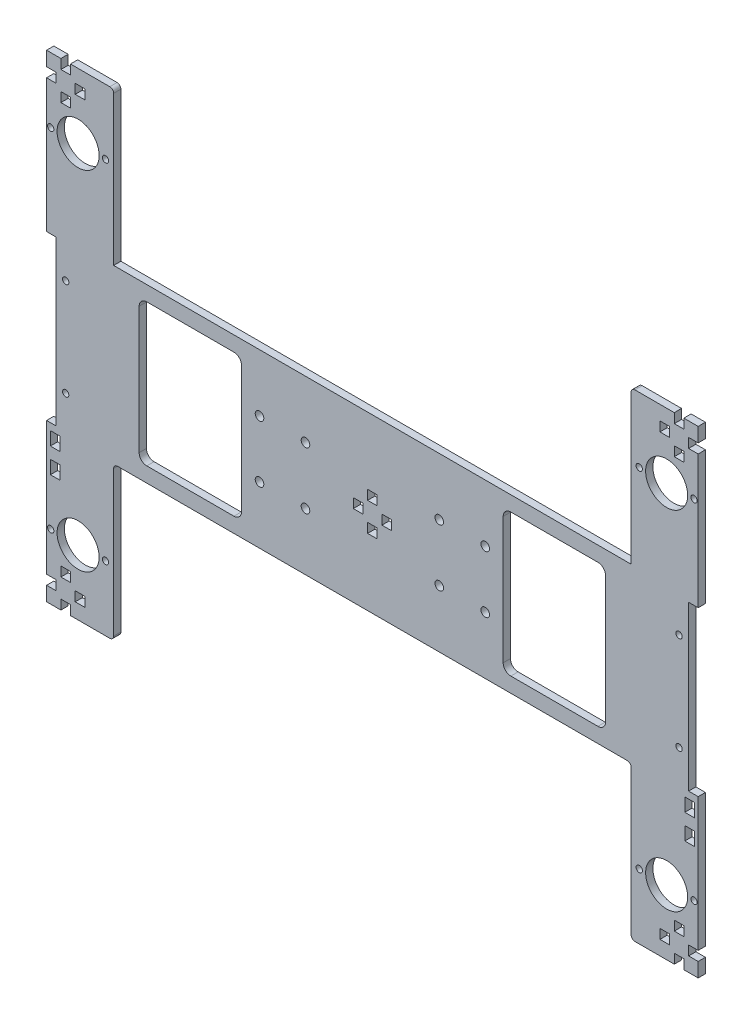
SolidWorks part; units mm, degrees
ref_plane "Front Plane" through (0, 0, 0) normal (0, 0, 1) x (1, 0, 0)
ref_plane "Top Plane" through (0, 0, 0) normal (0, 1, 0) x (1, 0, 0)
ref_plane "Right Plane" through (0, 0, 0) normal (1, 0, 0) x (0, 0, -1)
ref_plane "Plane1" through (0, 150, 0) normal (0, 1, 0) x (1, 0, 0)
ref_plane "Plane2" through (0, -150, 0) normal (0, 1, 0) x (1, 0, 0)
ref_plane "Plane3" through (150, 0, 0) normal (1, 0, 0) x (0, 0, -1)
ref_plane "Plane4" through (-150, 0, 0) normal (1, 0, 0) x (0, 0, -1)
sketch "Sketch2" plane through (0, 0, 0) normal (0, 0, 1) x (1, 0, 0)
  line L0 (0, -10.2) -> (0, 50.0764) construction
  line L5 (-59.06, 39.945) -> (-59.06, 10.055) construction
  line L23 (-170.5, 150) -> (-163, 150)
  line L24 (139.6652, 116) -> (168.3348, 116) construction
  line L31 (-170.5, -100) -> (-163, -100)
  line L40 (-152.1866, -81.0661) -> (-123.5266, -81.0661) construction
  line L42 (-135.4, 148) -> (-135.4, 70)
  line L43 (-135.4, 70) -> (135.4, 70)
  line L44 (135.4, 148) -> (135.4, 70)
  line L45 (137.4, 150) -> (158, 150)
  line L47 (-72.4574, 62.1714) -> (-118.0552, 62.1714)
  line L48 (72.4574, 62.1714) -> (118.0552, 62.1714)
  line L49 (68.4574, 58.1714) -> (68.4574, -8.1714)
  line L50 (72.4574, -12.1714) -> (118.0552, -12.1714)
  line L51 (122.0552, 58.1714) -> (122.0552, -8.1714)
  line L52 (68.4574, 62.1714) -> (122.0552, -12.1714) construction
  line L53 (68.4574, -12.1714) -> (122.0552, 62.1714) construction
  line L54 (-68.4574, 58.1714) -> (-68.4574, -8.1714)
  line L55 (-72.4574, -12.1714) -> (-118.0552, -12.1714)
  line L56 (-122.0552, 58.1714) -> (-122.0552, -8.1714)
  line L57 (177.1787, -66.0847) -> (177.1787, 11.9153) construction
  line L61 (165.5, 67.8042) -> (165.5, -17.8042)
  line L62 (165.5, -17.8042) -> (170.5, -17.8042)
  line L63 (170.5, 67.8042) -> (165.5, 67.8042)
  line L66 (177.1787, 0) -> (1253.7576, 0) construction
  line L67 (-165.5, 67.8042) -> (-165.5, -17.8042)
  line L70 (-160.5, 50.5) -> (-160.5, -0.5) construction
  line L71 (-170.5, 67.8042) -> (-165.5, 67.8042)
  line L72 (-170.5, -17.8042) -> (-165.5, -17.8042)
  line L74 (162.5, 25) -> (139.6652, 25) construction
  line L75 (-135.4, -98) -> (-135.4, -22)
  line L76 (-133.4, -20) -> (133.4, -20)
  line L77 (135.4, -22) -> (135.4, -98)
  line L78 (137.4, -100) -> (158, -100)
  line L126 (-2.5, 20) -> (2.5, 20)
  line L127 (2.5, 20) -> (2.5, 15)
  line L128 (2.5, 15) -> (-2.5, 15)
  line L129 (-2.5, 15) -> (-2.5, 20)
  line L130 (-10, 22.5) -> (-10, 27.5)
  line L131 (-10, 27.5) -> (-5, 27.5)
  line L132 (-5, 27.5) -> (-5, 22.5)
  line L133 (-5, 22.5) -> (-10, 22.5)
  line L134 (-2.5, 35) -> (2.5, 35)
  line L135 (2.5, 35) -> (2.5, 30)
  line L136 (2.5, 30) -> (-2.5, 30)
  line L137 (-2.5, 30) -> (-2.5, 35)
  line L138 (5, 22.5) -> (5, 27.5)
  line L139 (5, 27.5) -> (10, 27.5)
  line L140 (10, 27.5) -> (10, 22.5)
  line L141 (10, 22.5) -> (5, 22.5)
  line L142 (158, -95) -> (163, -95)
  line L143 (163, -95) -> (163, -100)
  line L145 (158, -100) -> (158, -95)
  line L146 (155.5, -87.5) -> (155.5, -92.5)
  line L147 (155.5, -92.5) -> (150.5, -92.5)
  line L148 (150.5, -92.5) -> (150.5, -87.5)
  line L149 (150.5, -87.5) -> (155.5, -87.5)
  line L150 (170.5, -17.8042) -> (170.5, -87.5)
  line L151 (170.5, -92.5) -> (165.5, -92.5)
  line L152 (165.5, -92.5) -> (165.5, -87.5)
  line L153 (165.5, -87.5) -> (170.5, -87.5)
  line L154 (158, -80) -> (163, -80)
  line L155 (163, -80) -> (163, -85)
  line L156 (163, -85) -> (158, -85)
  line L157 (158, -85) -> (158, -80)
  line L159 (-163, -100) -> (-163, -95)
  line L160 (-163, -95) -> (-158, -95)
  line L161 (-158, -95) -> (-158, -100)
  line L163 (-170.5, -87.5) -> (-165.5, -87.5)
  line L164 (-165.5, -87.5) -> (-165.5, -92.5)
  line L165 (-165.5, -92.5) -> (-170.5, -92.5)
  line L166 (-155.5, -92.5) -> (-155.5, -87.5)
  line L167 (-155.5, -87.5) -> (-150.5, -87.5)
  line L168 (-150.5, -87.5) -> (-150.5, -92.5)
  line L169 (-150.5, -92.5) -> (-155.5, -92.5)
  line L170 (-158, -85) -> (-163, -85)
  line L171 (-163, -85) -> (-163, -80)
  line L172 (-163, -80) -> (-158, -80)
  line L173 (-158, -80) -> (-158, -85)
  line L174 (-170.5, -17.8042) -> (-170.5, -87.5)
  line L175 (170.5, -92.5) -> (170.5, -100)
  line L176 (163, -100) -> (170.5, -100)
  line L177 (-170.5, -92.5) -> (-170.5, -100)
  line L178 (-158, -100) -> (-137.4, -100)
  line L179 (163, 150) -> (170.5, 150)
  line L180 (170.5, 142.5) -> (170.5, 150)
  line L181 (158, 135) -> (158, 130)
  line L182 (163, 135) -> (158, 135)
  line L183 (163, 130) -> (163, 135)
  line L184 (158, 130) -> (163, 130)
  line L185 (165.5, 137.5) -> (170.5, 137.5)
  line L186 (165.5, 142.5) -> (165.5, 137.5)
  line L187 (170.5, 142.5) -> (165.5, 142.5)
  line L188 (150.5, 137.5) -> (155.5, 137.5)
  line L189 (150.5, 142.5) -> (150.5, 137.5)
  line L190 (155.5, 142.5) -> (150.5, 142.5)
  line L191 (155.5, 137.5) -> (155.5, 142.5)
  line L192 (158, 150) -> (158, 145)
  line L193 (163, 145) -> (163, 150)
  line L194 (158, 145) -> (163, 145)
  line L195 (170.5, 67.8042) -> (170.5, 137.5)
  line L196 (-170.5, 67.8042) -> (-170.5, 137.5)
  line L197 (-170.5, 142.5) -> (-170.5, 150)
  line L198 (-158, 130) -> (-158, 135)
  line L199 (-163, 130) -> (-158, 130)
  line L200 (-163, 135) -> (-163, 130)
  line L201 (-158, 135) -> (-163, 135)
  line L202 (-150.5, 142.5) -> (-155.5, 142.5)
  line L203 (-150.5, 137.5) -> (-150.5, 142.5)
  line L204 (-155.5, 137.5) -> (-150.5, 137.5)
  line L205 (-155.5, 142.5) -> (-155.5, 137.5)
  line L206 (-165.5, 142.5) -> (-170.5, 142.5)
  line L207 (-165.5, 137.5) -> (-165.5, 142.5)
  line L208 (-170.5, 137.5) -> (-165.5, 137.5)
  line L209 (-158, 145) -> (-158, 150)
  line L210 (-163, 145) -> (-158, 145)
  line L211 (-163, 150) -> (-163, 145)
  line L212 (-170.5, 150) -> (-163, 150)
  line L213 (163, 150) -> (170.5, 150)
  line L214 (-158, 150) -> (-137.4, 150)
  line L216 (-163.5, -21.4) -> (-168.5, -21.4)
  line L217 (-163.5, -21.4) -> (-163.5, -28.4)
  line L218 (-163.5, -28.4) -> (-168.5, -28.4)
  line L219 (-168.5, -21.4) -> (-168.5, -28.4)
  line L220 (-163.5, -34.4) -> (-168.5, -34.4)
  line L221 (-163.5, -34.4) -> (-163.5, -41.4)
  line L222 (-163.5, -41.4) -> (-168.5, -41.4)
  line L223 (-168.5, -34.4) -> (-168.5, -41.4)
  line L224 (168.5, -21.4) -> (163.5, -21.4)
  line L225 (168.5, -21.4) -> (168.5, -28.4)
  line L226 (168.5, -28.4) -> (163.5, -28.4)
  line L227 (163.5, -21.4) -> (163.5, -28.4)
  line L228 (168.5, -34.4) -> (163.5, -34.4)
  line L229 (168.5, -34.4) -> (168.5, -41.4)
  line L230 (168.5, -41.4) -> (163.5, -41.4)
  line L231 (163.5, -34.4) -> (163.5, -41.4)
  circle A1 centre (-168.3348, 116) radius 1.65
  circle A2 centre (-139.6652, 116) radius 1.65
  circle A3 centre (168.3348, 116) radius 1.65
  circle A4 centre (139.6652, 116) radius 1.65
  circle A9 centre (154, 116) radius 11
  circle A10 centre (-154, 116) radius 11
  circle A17 centre (160.5, -0.5) radius 1.65
  circle A18 centre (160.5, 50.5) radius 1.65
  circle A19 centre (-160.5, -0.5) radius 1.65
  circle A20 centre (-160.5, 50.5) radius 1.65
  circle A27 centre (-35, 10.055) radius 2.25
  circle A32 centre (-35, 39.945) radius 2.25
  circle A33 centre (-59.06, 39.945) radius 2.25
  circle A34 centre (-59.06, 10.055) radius 2.25
  circle A35 centre (59.06, 10.055) radius 2.25
  circle A36 centre (35, 10.055) radius 2.25
  circle A37 centre (35, 39.945) radius 2.25
  circle A38 centre (59.06, 39.945) radius 2.25
  arc A46 (135.4, 148) -> (137.4, 150) centre (137.4, 148) cw
  arc A47 (-135.4, 148) -> (-137.4, 150) centre (-137.4, 148) ccw
  arc A48 (68.4574, -8.1714) -> (72.4574, -12.1714) centre (72.4574, -8.1714) ccw
  arc A49 (118.0552, -12.1714) -> (122.0552, -8.1714) centre (118.0552, -8.1714) ccw
  arc A50 (118.0552, 62.1714) -> (122.0552, 58.1714) centre (118.0552, 58.1714) cw
  arc A51 (72.4574, 62.1714) -> (68.4574, 58.1714) centre (72.4574, 58.1714) ccw
  arc A52 (-118.0552, 62.1714) -> (-122.0552, 58.1714) centre (-118.0552, 58.1714) ccw
  arc A53 (-72.4574, 62.1714) -> (-68.4574, 58.1714) centre (-72.4574, 58.1714) cw
  arc A54 (-68.4574, -8.1714) -> (-72.4574, -12.1714) centre (-72.4574, -8.1714) cw
  arc A55 (-118.0552, -12.1714) -> (-122.0552, -8.1714) centre (-118.0552, -8.1714) cw
  circle A68 centre (168.3348, -66) radius 1.65
  circle A69 centre (139.6652, -66) radius 1.65
  circle A70 centre (154, -66) radius 11
  circle A71 centre (-154, -66) radius 11
  circle A72 centre (-139.6652, -66) radius 1.65
  circle A73 centre (-168.3348, -66) radius 1.65
  arc A74 (135.4, -98) -> (137.4, -100) centre (137.4, -98) ccw
  arc A75 (133.4, -20) -> (135.4, -22) centre (133.4, -22) cw
  arc A76 (-135.4, -22) -> (-133.4, -20) centre (-133.4, -22) cw
  arc A77 (-135.4, -98) -> (-137.4, -100) centre (-137.4, -98) cw
  point P0 (0, 0)
  point P2 (0, 0)
  point P4 (0, 150)
  point P11 (-160.5, 25)
  point P12 (95.2563, 25)
  point P23 (-59.06, 25)
  point P24 (135.4, -100)
  point P39 (-165.5, 25)
  point P45 (135.4, 150)
  point P82 (177.1787, -27.0847)
  point P111 (-122.0552, 25)
  point P132 (-68.4574, 25)
  dimension "D3" = 51
  dimension "D7" = 34
  dimension "D8" = 3.3
  dimension "D10" = 22
  dimension "D11" = 74.3428
  dimension "D12" = 135.4
  dimension "D13" = 53.5977
  dimension "D16" = 68.4574
  dimension "D19" = 3.3
  dimension "D6" = 14.3348
  dimension "D20" = 14.3348
  dimension "D21" = 2
  dimension "D23" = 4.5
  dimension "D25" = 4.5
  dimension "D26" = 4.5
  dimension "D27" = 29.89
  dimension "D29" = 24.06
  dimension "D31" = 4
  dimension "D34" = 135.4
  dimension "D35" = 85.6084
  dimension "D37" = 80
  dimension "D4" = 3.3
  dimension "D5" = 5
  dimension "D22" = 29.89
  dimension "D28" = 24.06
  dimension "D30" = 35
  dimension "D15" = 2
  dimension "D14" = 45
extrude "Boss-Extrude1" add sketch "Sketch2" along normal blind 3.8
